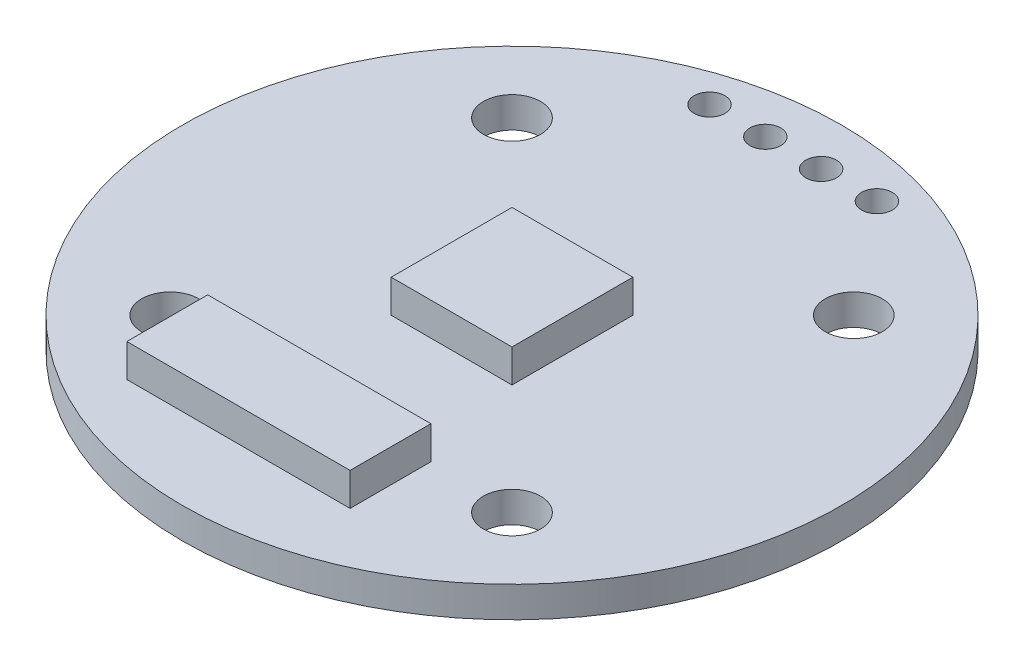
SolidWorks part; units mm, degrees
ref_plane "前视基准面" through (0, 0, 0) normal (0, 0, 1) x (1, 0, 0)
ref_plane "上视基准面" through (0, 0, 0) normal (0, 1, 0) x (1, 0, 0)
ref_plane "右视基准面" through (0, 0, 0) normal (1, 0, 0) x (0, 0, -1)
sketch "草图1" plane through (0, 0, 0) normal (0, 1, 0) x (1, 0, 0)
  line L0 (-5.4786, 0) -> (0, 0) construction
  line L1 (0, 0) -> (-7.7782, 7.7782)
  line L2 (0, 22.5184) -> (0, -17.9256) construction
  circle A0 centre (0, 0) radius 15
  circle A5 centre (-7.7782, 7.7782) radius 1.3
  circle A6 centre (7.7782, 7.7782) radius 1.3
  circle A7 centre (7.7782, -7.7782) radius 1.3
  circle A8 centre (-7.7782, -7.7782) radius 1.3
  circle A9 centre (-3.81, 12.8) radius 0.7
  circle A10 centre (-1.27, 12.8) radius 0.7
  circle A11 centre (1.27, 12.8) radius 0.7
  circle A12 centre (3.81, 12.8) radius 0.7
  point P14 (0, 0)
  point P16 (0, 0)
  dimension "D1" = 30
  dimension "D2" = 2.6
  dimension "D4" = 1.4
  dimension "D3" = 11
  dimension "D5" = 45
  dimension "D6" = 4
  dimension "D7" = 12.8
  dimension "D9" = 4
extrude "凸台-拉伸2" add sketch "草图1" along normal blind 1.4
sketch "草图2" plane through (0, 1.4, 0) normal (0, 1, 0) x (1, 0, 0)
  line L1 (-3.4, 16.33) -> (3.4, 16.33)
  line L2 (-3.4, 16.33) -> (-3.4, 12.13)
  line L3 (-3.4, 12.13) -> (3.4, 12.13)
  line L4 (3.4, 16.33) -> (3.4, 12.13)
  line L5 (2.75, -2.75) -> (-2.75, -2.75)
  line L6 (2.75, -2.75) -> (2.75, 2.75)
  line L7 (2.75, 2.75) -> (-2.75, 2.75)
  line L8 (-2.75, -2.75) -> (-2.75, 2.75)
  line L9 (2.75, -2.75) -> (-2.75, 2.75) construction
  line L10 (2.75, 2.75) -> (-2.75, -2.75) construction
  line L11 (-6.23, -7.62) -> (3.93, -7.62)
  line L12 (-6.23, -7.62) -> (-6.23, -11.3)
  line L13 (-6.23, -11.3) -> (3.93, -11.3)
  line L14 (3.93, -7.62) -> (3.93, -11.3)
  point P4 (0, 0)
  dimension "D1" = 4.2
  dimension "D2" = 6.8
  dimension "D3" = 12.13
  dimension "D4" = 3.4
  dimension "D5" = 5.5
  dimension "D6" = 3.68
  dimension "D7" = 10.16
  dimension "D8" = 7.62
  dimension "D9" = 3.93
extrude "凸台-拉伸5" add sketch "草图2" along normal blind 1.5 contours L8 L5 L6 L7 | L14 L11 L12 L13
sketch "草图3" plane through (0, 0, 0) normal (0, -1, 0) x (1, 0, 0)
  line L5 (-12.24, -2.67) -> (-16.64, -2.67)
  line L6 (-12.24, -2.67) -> (-12.24, 2.67)
  line L7 (-12.24, 2.67) -> (-16.64, 2.67)
  line L8 (-16.64, -2.67) -> (-16.64, 2.67)
  line L9 (2.5, -1.685) -> (-2.5, -1.685)
  line L10 (2.5, -1.685) -> (2.5, 1.685)
  line L11 (2.5, 1.685) -> (-2.5, 1.685)
  line L12 (-2.5, -1.685) -> (-2.5, 1.685)
  line L13 (2.5, -1.685) -> (-2.5, 1.685) construction
  line L14 (2.5, 1.685) -> (-2.5, -1.685) construction
  point P8 (0, 0)
  dimension "D1" = 5
  dimension "D2" = 3.37
  dimension "D3" = 4.4
  dimension "D4" = 5.34
  dimension "D5" = 12.24
  dimension "D6" = 2.67
extrude "凸台-拉伸7" add sketch "草图3" along normal blind 1.5 contours L12 L9 L10 L11
